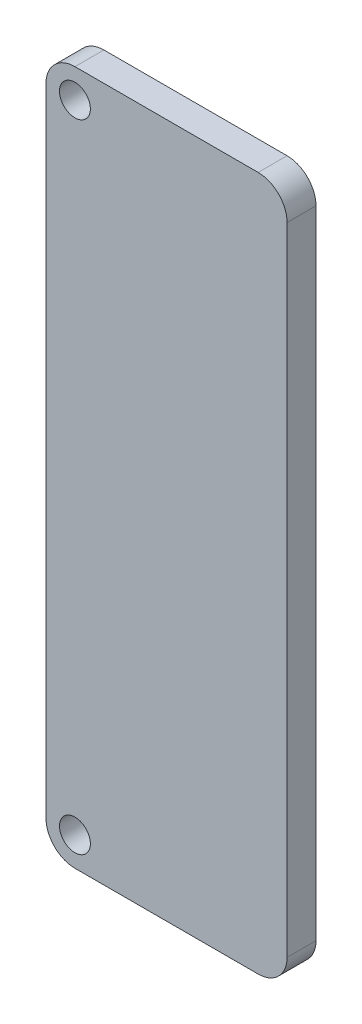
SolidWorks part; units mm, degrees
ref_plane "Front Plane" through (0, 0, 0) normal (0, 0, 1) x (1, 0, 0)
ref_plane "Top Plane" through (0, 0, 0) normal (0, 1, 0) x (1, 0, 0)
ref_plane "Right Plane" through (0, 0, 0) normal (1, 0, 0) x (0, 0, -1)
sketch "Sketch1" plane through (0, 0, 0) normal (0, 0, 1) x (1, 0, 0)
  line L0 (0, 36) -> (0, -36)
  line L1 (0, -36) -> (-22, -36)
  line L3 (0, 36) -> (-22, 36)
  line L4 (-25, -33) -> (-25, 33)
  line L5 (0, 0) -> (-25, 36) construction
  line L6 (0, 0) -> (-25, -36) construction
  arc A0 (-25, -33) -> (-22, -36) centre (-22, -33) ccw
  arc A1 (-25, 33) -> (-22, 36) centre (-22, 33) cw
  circle A2 centre (-22, 33) radius 1.6
  circle A3 centre (-22, -33) radius 1.6
  point P0 (0, 0)
  dimension "D1" = 3
  dimension "D4" = 3.2
  dimension "D2" = 72
  dimension "D3" = 25
extrude "Boss-Extrude1" add sketch "Sketch1" along normal blind 3
sketch "Sketch2" plane through (0, 0, 0) normal (0, 0, -1) x (-1, 0, 0)
  line L0 (24.4, 30) -> (12, 30)
  line L1 (12, 30) -> (12, -3)
  line L2 (12, -3) -> (3, -3)
  line L3 (3, -3) -> (3, -30.5)
  line L4 (3, -30.5) -> (24.4, -30.5)
  line L5 (24.4, -30.5) -> (24.4, 30)
  line L7 (25, 33) -> (25, -33) construction
  line L8 (22, -36) -> (0, -36) construction
  line L9 (0, 36) -> (22, 36) construction
  dimension "D1" = 0.6
  dimension "D2" = 5.5
  dimension "D3" = 6
  dimension "D4" = 22
  dimension "D5" = 13
  dimension "D6" = 33
extrude "Cut-Extrude1" cut sketch "Sketch2" against normal blind 2
sketch "Sketch3" plane through (0, 0, 0) normal (0, 0, -1) x (-1, 0, 0)
  line L0 (25, 33) -> (25, -33) construction
  line L1 (25, 4.25) -> (20, 4.25)
  line L2 (25, 4.25) -> (25, -4.25)
  line L3 (25, -4.25) -> (20, -4.25)
  line L4 (20, 4.25) -> (20, -4.25)
  point P6 (20, 0)
  point P7 (0, 0)
  dimension "D1" = 8.5
  dimension "D2" = 5
extrude "Cut-Extrude2" cut sketch "Sketch3" against normal blind 2.7
sketch "Sketch4" plane through (0, 0, 0) normal (0, 0, -1) x (-1, 0, 0)
  line L1 (25, 4.25) -> (21, 4.25)
  line L2 (25, 4.25) -> (25, 7.25)
  line L3 (25, 7.25) -> (21, 7.25)
  line L4 (21, 4.25) -> (21, 7.25)
  dimension "D1" = 3
  dimension "D2" = 4
extrude "Boss-Extrude2" add sketch "Sketch4" against normal up to surface (2 mm away) up to face at (-16.76, -0.7, 2)
fillet "Fillet1" radius 3 2 edges at (0, -36, 1.5) (0, 36, 1.5)
